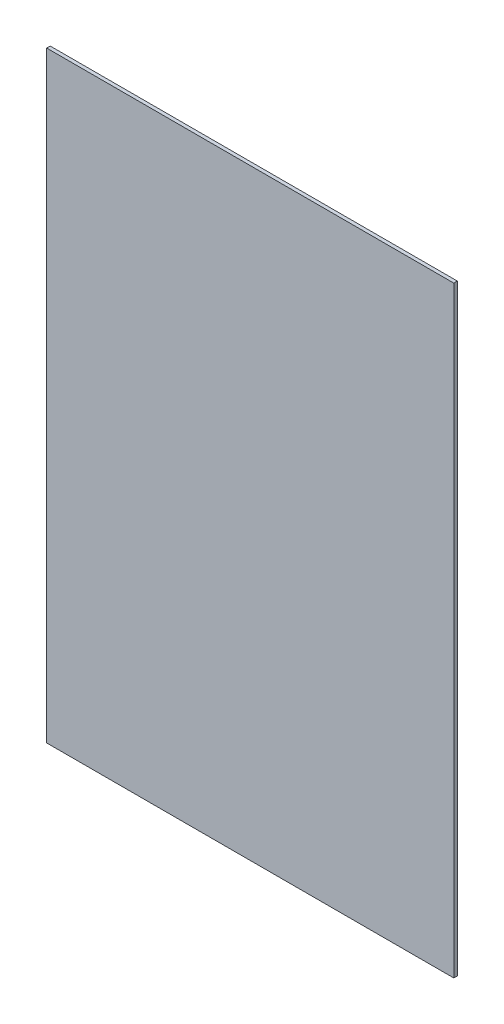
SolidWorks part; units mm, degrees
material "6061-T6 (SS)"
ref_plane "Alzado" through (0, 0, 0) normal (0, 0, 1) x (1, 0, 0)
ref_plane "Planta" through (0, 0, 0) normal (0, 1, 0) x (1, 0, 0)
ref_plane "Vista lateral" through (0, 0, 0) normal (1, 0, 0) x (0, 0, -1)
sketch "Sketch2" plane through (0, 0, 0) normal (0, 0, 1) x (1, 0, 0)
  line L1 (-115, 170) -> (115, 170)
  line L2 (-115, 170) -> (-115, -170)
  line L3 (-115, -170) -> (115, -170)
  line L4 (115, 170) -> (115, -170)
  line L5 (-115, 170) -> (115, -170) construction
  line L6 (-115, -170) -> (115, 170) construction
  point P0 (0, 0)
  dimension "D1" = 340
  dimension "D2" = 230
extrude "Boss-Extrude1" add sketch "Sketch2" along normal blind 2
